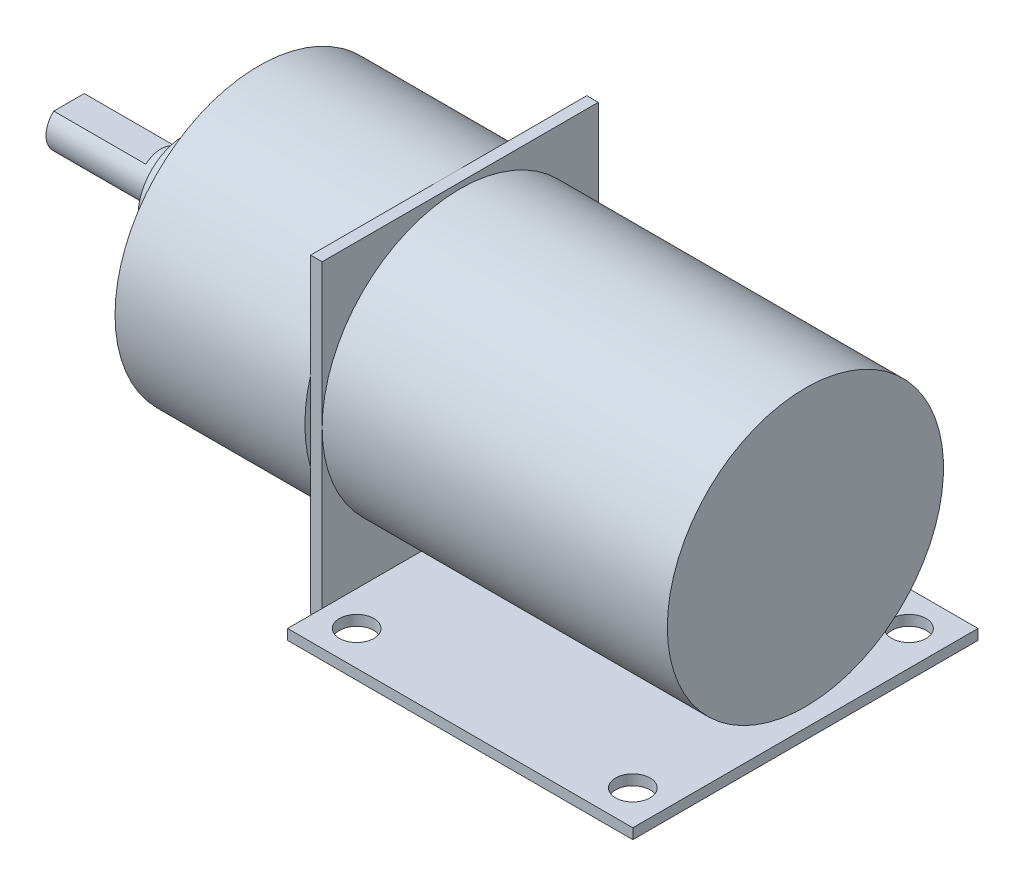
SolidWorks part; units mm, degrees
ref_plane "Front Plane" through (0, 0, 0) normal (0, 0, 1) x (1, 0, 0)
ref_plane "Top Plane" through (0, 0, 0) normal (0, 1, 0) x (1, 0, 0)
ref_plane "Right Plane" through (0, 0, 0) normal (1, 0, 0) x (0, 0, -1)
sketch "Sketch1" plane through (0, 0, 0) normal (0, 1, 0) x (1, 0, 0)
  line L1 (15, -15) -> (-15, -15)
  line L2 (15, -15) -> (15, 15)
  line L3 (15, 15) -> (-15, 15)
  line L4 (-15, -15) -> (-15, 15)
  line L5 (15, -15) -> (-15, 15) construction
  line L6 (15, 15) -> (-15, -15) construction
  line L7 (12, -12) -> (-12, -12) construction
  line L8 (12, -12) -> (12, 12) construction
  line L9 (12, 12) -> (-12, 12) construction
  line L10 (-12, -12) -> (-12, 12) construction
  line L11 (12, -12) -> (-12, 12) construction
  line L12 (12, 12) -> (-12, -12) construction
  circle A0 centre (-12, 12) radius 1.5
  circle A1 centre (12, 12) radius 1.5
  circle A2 centre (12, -12) radius 1.5
  circle A3 centre (-12, -12) radius 1.5
  point P0 (0, 0)
  point P6 (0, 0)
  dimension "D5" = 3
  dimension "D1" = 30
  dimension "D2" = 30
  dimension "D3" = 24
  dimension "D4" = 24
extrude "Boss-Extrude2" add sketch "Sketch1" along normal blind 0.9
sketch "Sketch9" plane through (0, 0, 0) normal (0, 1, 0) x (1, 0, 0)
  line L0 (-15, 15) -> (-15, -15) construction
  line L5 (-15, -12) -> (-16, -12)
  line L6 (-15, -12) -> (-15, 12)
  line L7 (-15, 12) -> (-16, 12)
  line L8 (-16, -12) -> (-16, 12)
  point P8 (-15, 0)
  point P9 (-15, 0)
  dimension "D1" = 24
  dimension "D2" = 1
extrude "Boss-Extrude3" add sketch "Sketch9" along normal blind 27
sketch "Sketch10" plane through (-15, 0, 0) normal (1, 0, 0) x (0, 0, -1)
  circle A0 centre (0, 14.5) radius 12
  point P2 (-5.4483, 13.4375)
  dimension "D1" = 24
  dimension "D2" = 14.5
extrude "Boss-Extrude4" add sketch "Sketch10" along normal up to surface (30 mm away) up to face at (15, 0.45, 0)
sketch "Sketch11" plane through (-16, 0, 0) normal (-1, 0, 0) x (0, 0, 1)
  circle A0 centre (0, 14.5) radius 12.5
  arc A1 (12, 14.5) -> (-12, 14.5) centre (0, 14.5) ccw construction
  point P2 (0, 0)
  dimension "D1" = 25
extrude "Boss-Extrude5" add sketch "Sketch11" along normal blind 16.5
sketch "Sketch12" plane through (-32.5, 0, 0) normal (-1, 0, 0) x (0, 0, 1)
  circle A0 centre (0, 14.5) radius 4
  circle A1 centre (0, 14.5) radius 12.5 construction
  dimension "D1" = 8
extrude "Boss-Extrude6" add sketch "Sketch12" along normal blind 6.5
sketch "Sketch13" plane through (-39, 0, 0) normal (-1, 0, 0) x (0, 0, 1)
  circle A0 centre (0, 14.5) radius 2
  circle A1 centre (0, 14.5) radius 4 construction
  dimension "D1" = 4
extrude "Boss-Extrude7" add sketch "Sketch13" along normal blind 10
sketch "Sketch14" plane through (-49, 0, 0) normal (-1, 0, 0) x (0, 0, 1)
  line L0 (-1.3229, 16) -> (1.3229, 16)
  line L1 (0, 16) -> (0, 12.5) construction
  circle A0 centre (0, 14.5) radius 2 construction
  circle A1 centre (0, 14.5) radius 2 construction
  circle A3 centre (0, 14.5) radius 2
  arc A4 (1.3229, 16) -> (-1.3229, 16) centre (0, 14.5) ccw
  dimension "D1" = 3.5
  dimension "D2" = 0
extrude "Cut-Extrude1" cut sketch "Sketch14" against normal blind 8
